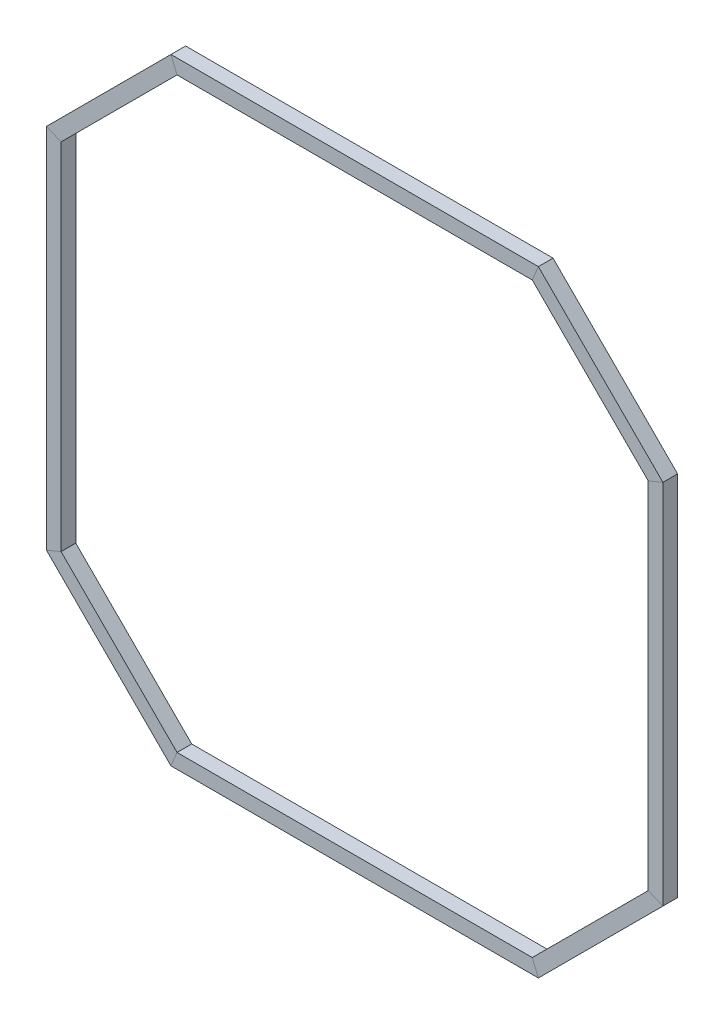
SolidWorks part; units mm, degrees
ref_plane "前视基准面" through (0, 0, 0) normal (0, 0, 1) x (1, 0, 0)
ref_plane "上视基准面" through (0, 0, 0) normal (0, 1, 0) x (1, 0, 0)
ref_plane "右视基准面" through (0, 0, 0) normal (1, 0, 0) x (0, 0, -1)
sketch "草图1" plane through (0, 0, 0) normal (0, 0, -1) x (1, 0, 0)
  line L0 (-125.1472, 209.8528) -> (125.1472, 209.8528)
  line L1 (-125.1472, 209.8528) -> (-210, 125)
  line L2 (-210, 125) -> (-210, -125)
  line L3 (-210, -125) -> (-125.1472, -209.8528)
  line L4 (0, 0) -> (0, 362.4389) construction
  line L5 (210, -125) -> (125.1472, -209.8528)
  line L6 (210, 125) -> (210, -125)
  line L7 (125.1472, 209.8528) -> (210, 125)
  line L9 (-125.1472, -209.8528) -> (125.1472, -209.8528)
  line L10 (210, 0) -> (0, 0) construction
  dimension "D1" = 250
  dimension "D2" = 420
  dimension "D3" = 45
  dimension "D4" = 45
  dimension "D5" = 120
other "结构构件1"
ref_plane "基准面1" through (-125.1472, -204.8528, -5) normal (1, 0, 0) x (0, 1, 0)
sketch "Sketch11" plane through (-125.1472, -204.8528, -5) normal (1, 0, 0) x (0, 1, 0)
  line L0 (-4, 4) -> (4, 4)
  line L1 (-5, -5) -> (5, -5)
  line L2 (-5, -5) -> (-5, 5)
  line L3 (-5, 5) -> (5, 5)
  line L4 (5, -5) -> (5, 5)
  line L5 (-5, -5) -> (5, 5) construction
  line L6 (-5, 5) -> (5, -5) construction
  line L7 (4, -4) -> (4, 4)
  line L8 (-4, -4) -> (4, -4)
  line L9 (-4, -4) -> (-4, 4)
  line L10 (-5, 0) -> (5, 0) construction
  line L11 (0, -5) -> (0, 5) construction
  point P0 (0, 0)
  point P13 (0, 0)
  point P14 (0, 5)
  point P15 (5, 0)
  point P16 (0, -5)
  point P17 (-5, 0)
  point P18 (-5, -5)
  point P19 (-5, 5)
  point P20 (5, 5)
  point P21 (5, -5)
  dimension "D1" = 10
  dimension "D2" = 10
  dimension "D3" = 1
